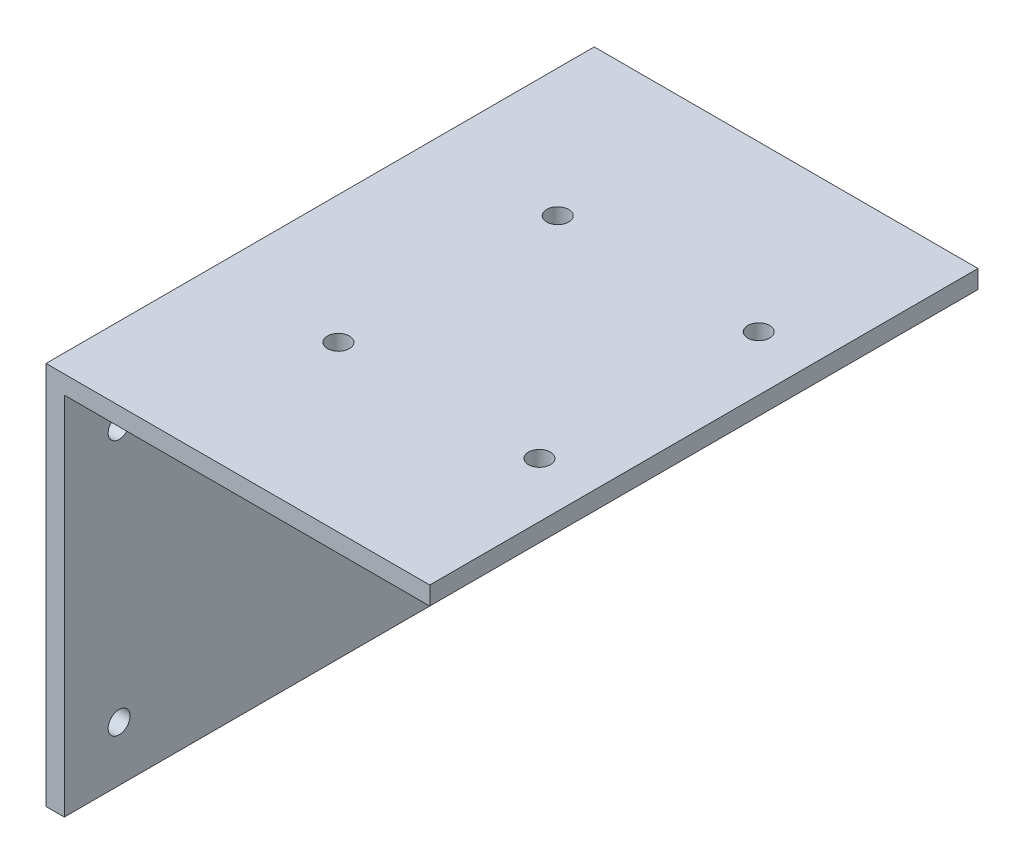
SolidWorks part; units mm, degrees
ref_plane "Front Plane" through (0, 0, 0) normal (0, 0, 1) x (1, 0, 0)
ref_plane "Top Plane" through (0, 0, 0) normal (0, 1, 0) x (1, 0, 0)
ref_plane "Right Plane" through (0, 0, 0) normal (1, 0, 0) x (0, 0, -1)
sketch "Sketch1" plane through (0, 0, 0) normal (0, 0, 1) x (1, 0, 0)
  line L0 (0, 0) -> (0, 105)
  line L1 (0, 105) -> (105, 105)
  line L2 (105, 105) -> (105, 100)
  line L3 (105, 100) -> (5, 100)
  line L4 (5, 100) -> (5, 0)
  line L5 (5, 0) -> (0, 0)
  dimension "D1" = 5
  dimension "D2" = 5
  dimension "D3" = 100
  dimension "D4" = 100
extrude "Boss-Extrude1" add sketch "Sketch1" along normal blind 150
sketch "Sketch2" plane through (5, 0, 0) normal (1, 0, 0) x (0, 0, -1)
  line L0 (-150, 50) -> (-75, 50) construction
  line L1 (-150, 0) -> (-150, 100) construction
  line L2 (-75, 50) -> (-75, 100) construction
  line L3 (-150, 100) -> (0, 100) construction
  circle A0 centre (-135, 85) radius 3
  circle A1 centre (-15, 85) radius 3
  circle A2 centre (-15, 15) radius 3
  circle A3 centre (-135, 15) radius 3
  dimension "D1" = 70
  dimension "D2" = 120
  dimension "D3" = 6
extrude "Cut-Extrude1" cut sketch "Sketch2" against normal up to next
sketch "Sketch3" plane through (0, 100, 0) normal (0, -1, 0) x (1, 0, 0)
  line L2 (55, 75) -> (105, 75) construction
  line L3 (105, 150) -> (105, 0) construction
  circle A0 centre (35, 105) radius 3
  circle A1 centre (90, 105) radius 3
  circle A2 centre (90, 45) radius 3
  circle A3 centre (35, 45) radius 3
  point P0 (0, 0)
  dimension "D1" = 60
  dimension "D2" = 55
  dimension "D3" = 6
  dimension "D4" = 15
extrude "Cut-Extrude2" cut sketch "Sketch3" against normal up to next
